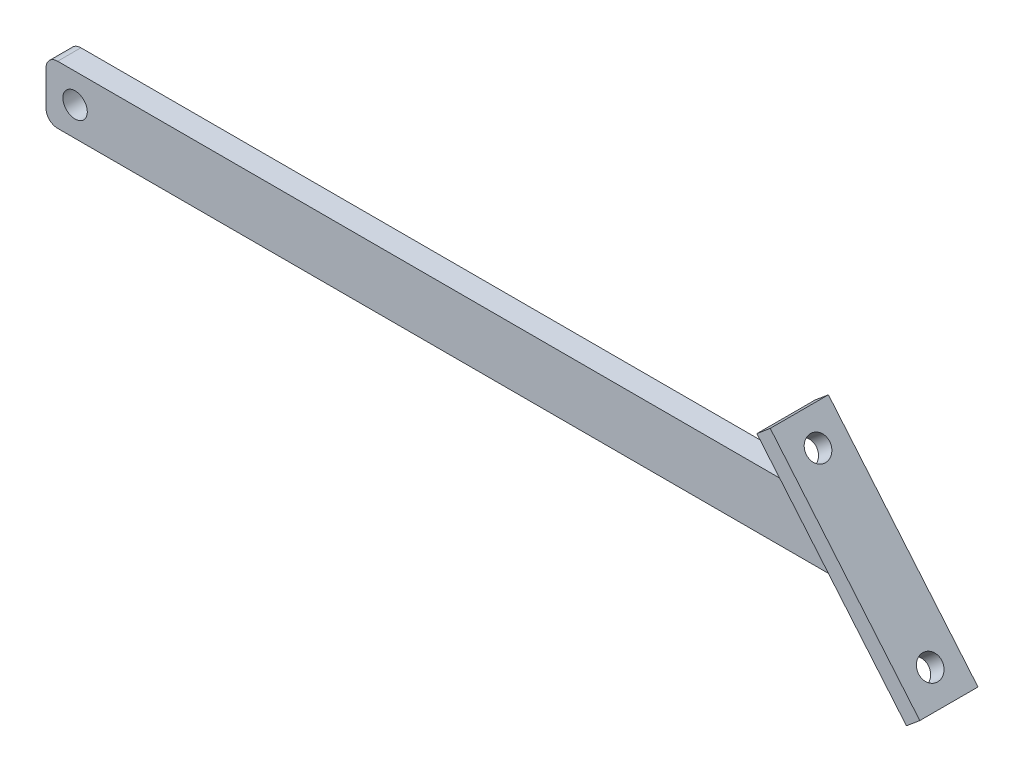
SolidWorks part; units mm, degrees
ref_plane "前视基准面" through (0, 0, 0) normal (0, 0, 1) x (1, 0, 0)
ref_plane "上视基准面" through (0, 0, 0) normal (0, 1, 0) x (1, 0, 0)
ref_plane "右视基准面" through (0, 0, 0) normal (1, 0, 0) x (0, 0, -1)
sketch "草图1" plane through (0, 0, 0) normal (0, 0, 1) x (1, 0, 0)
  line L0 (125.1657, -4.7238) -> (116.7747, 5.2762)
  line L1 (-14.8343, 5.2762) -> (116.7747, 5.2762)
  line L2 (-14.8343, 5.2762) -> (-14.8343, -4.7238)
  line L3 (-14.8343, -4.7238) -> (125.1657, -4.7238)
  circle A0 centre (-9.8343, 0.2762) radius 2.1
  dimension "D5" = 4.2
  dimension "D1" = 10
  dimension "D2" = 140
  dimension "D3" = 5
  dimension "D4" = 5
  dimension "D6" = 50
extrude "凸台-拉伸1" add sketch "草图1" along normal blind 4
fillet "圆角1" radius 2 2 edges at (-14.8343, -4.7238, 2) (-14.8343, 5.2762, 2)
sketch "草图2" plane through (71.1243, 59.6804, 0) normal (0.766, 0.6428, 0) x (0, 0, -1)
  line L0 (0, -84.0736) -> (0, -71.0195) construction
  line L2 (-7, -101.0195) -> (-7, -61.0195)
  line L3 (-7, -101.0195) -> (3, -101.0195)
  line L4 (-4, -84.0736) -> (-4, -71.0195) construction
  line L5 (-4, -71.0195) -> (0, -71.0195) construction
  line L7 (-7, -61.0195) -> (3, -61.0195)
  line L9 (3, -61.0195) -> (3, -101.0195)
  circle A0 centre (-2, -66.0195) radius 2
  circle A1 centre (-2, -96.0195) radius 2
  point P14 (-4, -77.5466)
  dimension "D4" = 4
  dimension "D7" = 4
  dimension "D1" = 40
  dimension "D2" = 5
  dimension "D3" = 5
  dimension "D5" = 3
  dimension "D6" = 3
  dimension "D8" = 10
  dimension "D9" = 5
  dimension "D10" = 5
extrude "凸台-拉伸2" add sketch "草图2" along normal blind 3
